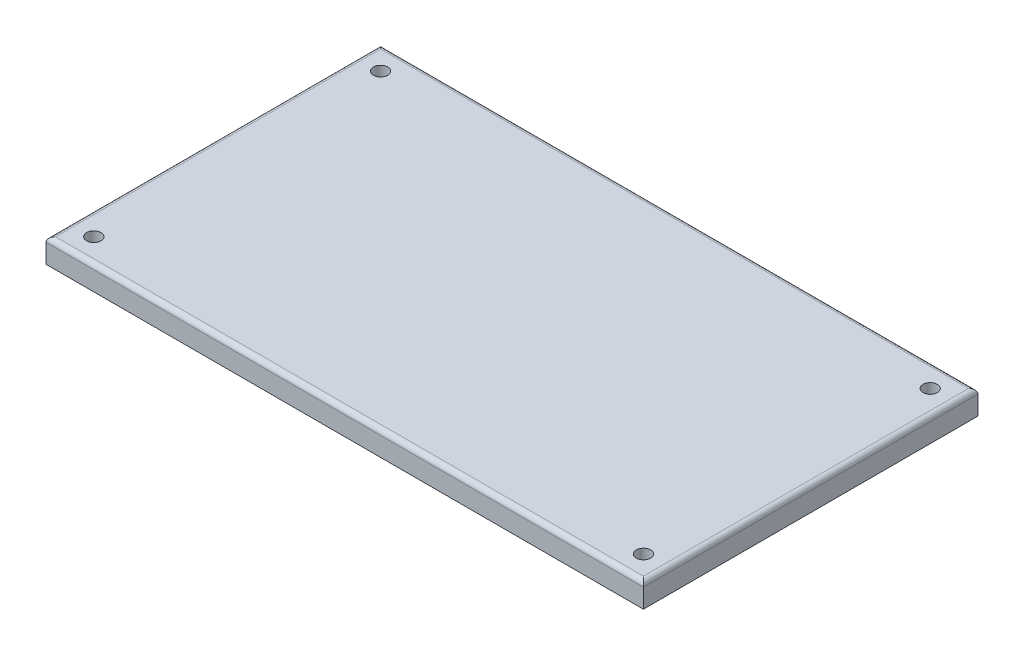
SolidWorks part; units mm, degrees
ref_plane "Front Plane" through (0, 0, 0) normal (0, 0, 1) x (1, 0, 0)
ref_plane "Top Plane" through (0, 0, 0) normal (0, 1, 0) x (1, 0, 0)
ref_plane "Right Plane" through (0, 0, 0) normal (1, 0, 0) x (0, 0, -1)
sketch "Sketch1" plane through (0, 0, 0) normal (0, 1, 0) x (1, 0, 0)
  line L1 (0, 0) -> (125, 0)
  line L2 (0, 0) -> (0, 70)
  line L3 (0, 70) -> (125, 70)
  line L4 (125, 0) -> (125, 70)
extrude "Boss-Extrude1" add sketch "Sketch1" along normal blind 5
fillet "Fillet1" radius 1 4 edges at (125, 5, -35) (62.5, 5, 0) (0, 5, -35) (62.5, 5, -70)
sketch "Sketch2" plane through (0, 5, 0) normal (0, 1, 0) x (1, 0, 0)
  line L0 (124, 1) -> (124, 5) construction
  line L1 (124, 1) -> (124, 69) construction
  line L2 (124, 5) -> (120, 5) construction
  line L3 (62.5, 1) -> (62.5, 69) construction
  line L4 (1, 1) -> (124, 1) construction
  line L5 (124, 69) -> (1, 69) construction
  line L6 (124, 35) -> (62.5, 35) construction
  circle A0 centre (120, 5) radius 1.5
  circle A1 centre (120, 65) radius 1.5
  circle A2 centre (5, 65) radius 1.5
  circle A3 centre (5, 5) radius 1.5
extrude "Cut-Extrude1" cut sketch "Sketch2" against normal up to next
